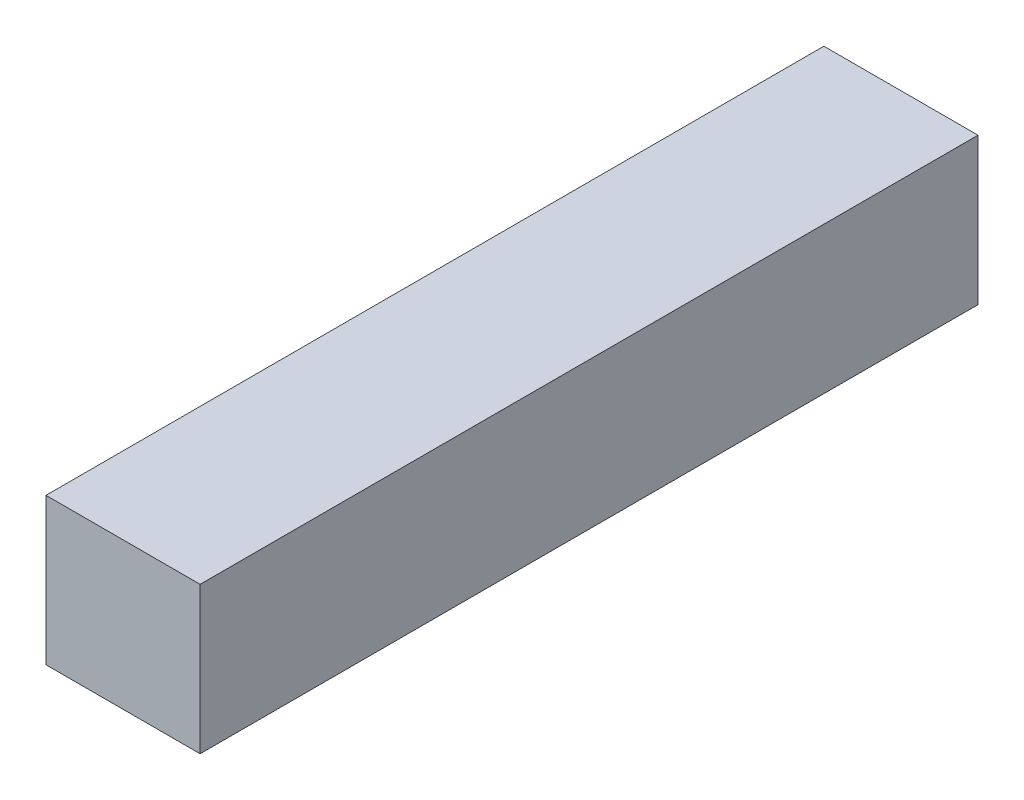
SolidWorks part; units mm, degrees
ref_plane "Plan de face" through (0, 0, 0) normal (0, 0, 1) x (1, 0, 0)
ref_plane "Plan de dessus" through (0, 0, 0) normal (0, 1, 0) x (1, 0, 0)
ref_plane "Plan de droite" through (0, 0, 0) normal (1, 0, 0) x (0, 0, -1)
sketch "Esquisse1" plane through (0, 0, 0) normal (0, 0, 1) x (1, 0, 0)
  line L1 (0, 0) -> (-63, 0)
  line L2 (0, 0) -> (0, 60)
  line L3 (0, 60) -> (-63, 60)
  line L4 (-63, 0) -> (-63, 60)
  dimension "D1" = 60
  dimension "D2" = 63
extrude "Boss.-Extru.1" add sketch "Esquisse1" along normal blind 318
